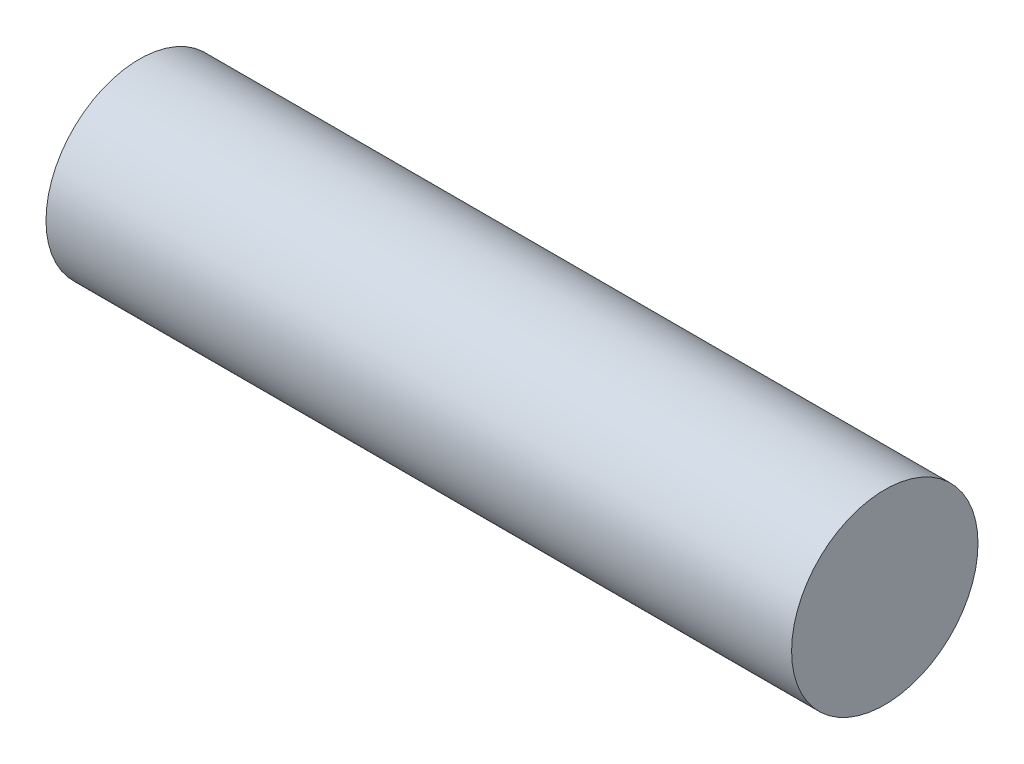
SolidWorks part; units mm, degrees
ref_plane "Front Plane" through (0, 0, 0) normal (1, 0, 0) x (0, 1, 0)
ref_plane "Top Plane" through (0, 0, 0) normal (0, 0, 1) x (0, 1, 0)
ref_plane "Right Plane" through (0, 0, 0) normal (0, 1, 0) x (-1, 0, 0)
sketch "Sketch1" plane through (0, 0, 0) normal (1, 0, 0) x (0, 1, 0)
  circle A0 centre (0, 0) radius 3.175
  dimension "D1" = 6.35
extrude "Boss-Extrude1" add sketch "Sketch1" along normal blind 25.4
equation "\"shaft_len\"= 1in"
equation "\"ouput_shaft_d\"= 0.25"
equation "\"input_shaft_d\" = 0.125in"
equation "\"pinion_pitch\"= 3 / 8in"
equation "\"gear_pitch\"= 1in"
equation "\"pitch_tot\"= \"pinion_pitch\" + \"gear_pitch\""
equation "\"sleeve_len\"= 3 / 8in"
equation "\"pinion_sleeve_d\"= 1 / 4in"
equation "\"gear_sleeve_d\"= 3 / 8in"
equation "\"D1@Sketch1\"=\"ouput_shaft_d\""
equation "\"D1@Boss-Extrude1\"=\"shaft_len\""
